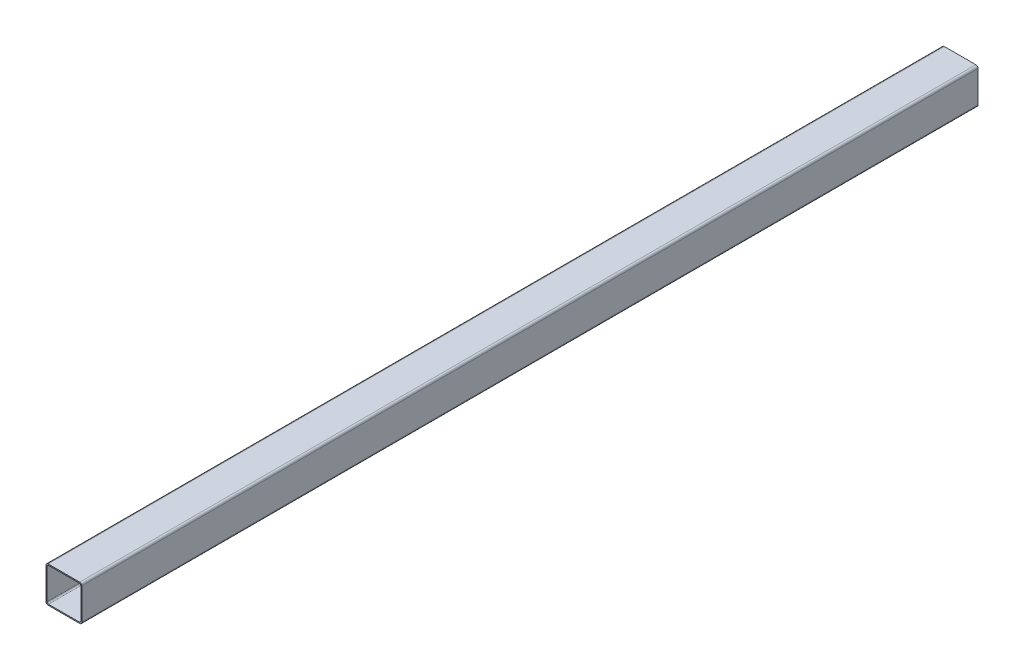
SolidWorks part; units mm, degrees
material "AISI 1020"
ref_plane "Спереди" through (0, 0, 0) normal (0, 0, 1) x (1, 0, 0)
ref_plane "Сверху" through (0, 0, 0) normal (0, 1, 0) x (1, 0, 0)
ref_plane "Справа" through (0, 0, 0) normal (1, 0, 0) x (0, 0, -1)
sketch "Эскиз1" plane through (0, 0, 0) normal (0, 0, 1) x (1, 0, 0)
  line B0 (-44, 50) -> (44, 50)
  line B1 (-50, 44) -> (-50, -44)
  line B2 (-44, -50) -> (44, -50)
  line B3 (50, 44) -> (50, -44)
  line B4 (-50, 50) -> (50, -50) construction
  line B5 (-50, -50) -> (50, 50) construction
  line B6 (-43, 47) -> (43, 47)
  line B7 (-47, 43) -> (-47, -43)
  line B8 (-43, -47) -> (43, -47)
  line B9 (47, 43) -> (47, -43)
  line B10 (-47, 47) -> (47, -47) construction
  line B11 (-47, -47) -> (47, 47) construction
  arc B12 (-50, -44) -> (-44, -50) centre (-44, -44) ccw
  arc B13 (44, -50) -> (50, -44) centre (44, -44) ccw
  arc B14 (44, 50) -> (50, 44) centre (44, 44) cw
  arc B15 (-44, 50) -> (-50, 44) centre (-44, 44) ccw
  arc B16 (-47, -43) -> (-43, -47) centre (-43, -43) ccw
  arc B17 (43, -47) -> (47, -43) centre (43, -43) ccw
  arc B18 (43, 47) -> (47, 43) centre (43, 43) cw
  arc B19 (-43, 47) -> (-47, 43) centre (-43, 43) ccw
sketch_block_instance "Блок1-1"
sketch_block "Блок1" parameters "D3"=6, "D4"=4, "D1"=100, "D2"=3
extrude "Бобышка-Вытянуть1" add sketch "Эскиз1" against normal blind 2500
sketch "Эскиз2" [suppressed] plane through (0, 0, 0) normal (0, 0, 1) x (1, 0, 0)
  line L0 (-50, 44) -> (-50, -44) construction
  line L1 (-50, 3) -> (-3, 3)
  line L2 (-50, 3) -> (-50, -3)
  line L3 (-50, -3) -> (-3, -3)
  line L4 (50, 3) -> (50, -3)
  line L5 (50, -44) -> (50, 44) construction
  line L6 (44, 50) -> (-44, 50) construction
  line L7 (-3, 50) -> (3, 50)
  line L8 (-3, 50) -> (-3, 3)
  line L9 (-3, -50) -> (3, -50)
  line L10 (3, 50) -> (3, 3)
  line L11 (-44, -50) -> (44, -50) construction
  line L12 (3, 3) -> (50, 3)
  line L13 (3, -3) -> (50, -3)
  line L14 (-3, -3) -> (-3, -50)
  line L15 (3, -3) -> (3, -50)
  point P16 (0, -50)
  point P18 (50, 0)
  dimension "D1" = 6
extrude "Вырез-Вытянуть1" [suppressed] cut sketch "Эскиз2" against normal blind 100
